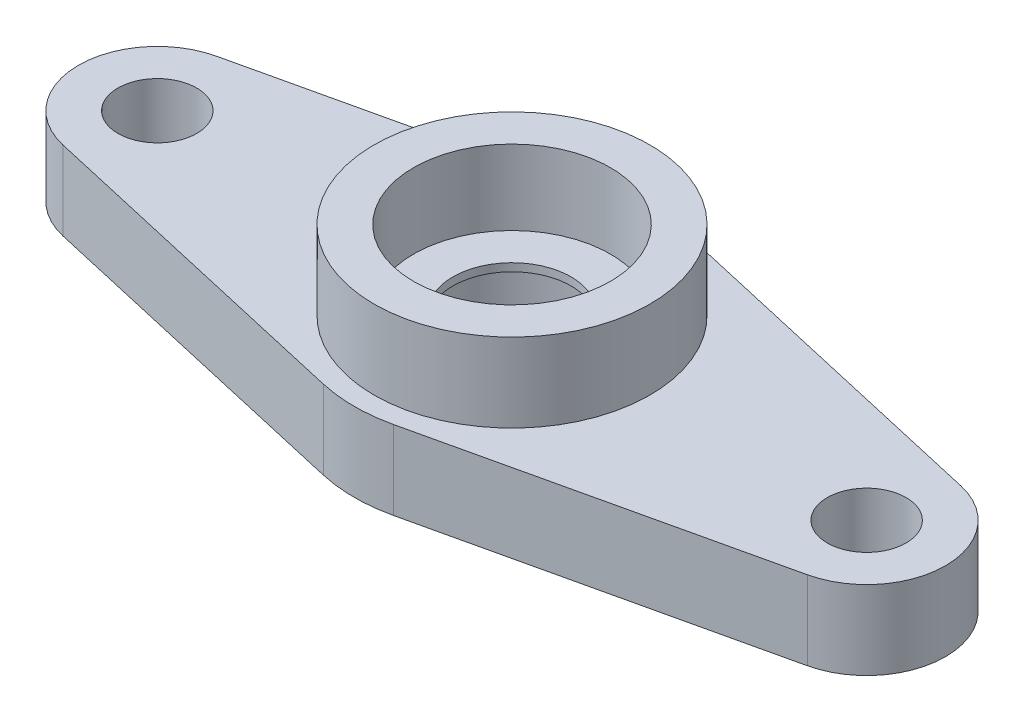
SolidWorks part; units mm, degrees
ref_plane "前基準面" through (0, 0, 0) normal (0, 0, 1) x (1, 0, 0)
ref_plane "上基準面" through (0, 0, 0) normal (0, 1, 0) x (1, 0, 0)
ref_plane "右基準面" through (0, 0, 0) normal (1, 0, 0) x (0, 0, -1)
sketch "草圖1" plane through (0, 0, 0) normal (0, 1, 0) x (1, 0, 0)
  line L0 (-9, 0) -> (9, 0) construction
  line L1 (-9.4444, 1.95) -> (-0.8889, 3.9)
  line L2 (-9.4444, -1.95) -> (-0.8889, -3.9)
  line L3 (0.8889, -3.9) -> (9.4444, -1.95)
  line L4 (0.8889, 3.9) -> (9.4444, 1.95)
  circle A0 centre (0, 0) radius 2.5
  circle A1 centre (-9, 0) radius 1
  circle A2 centre (9, 0) radius 1
  arc A3 (-0.8889, -3.9) -> (0.8889, -3.9) centre (0, 0) ccw
  arc A4 (-9.4444, 1.95) -> (-9.4444, -1.95) centre (-9, 0) ccw
  arc A5 (9.4444, -1.95) -> (9.4444, 1.95) centre (9, 0) ccw
  arc A6 (0.8889, 3.9) -> (-0.8889, 3.9) centre (0, 0) ccw
  dimension "D2" = 5
  dimension "D3" = 2
  dimension "D4" = 4
  dimension "D5" = 4
  dimension "D1" = 18
extrude "填料-伸長1" add sketch "草圖1" along normal blind 2
sketch "草圖2" plane through (0, 2, 0) normal (0, 1, 0) x (1, 0, 0)
  circle A0 centre (0, 0) radius 3.5
  circle A1 centre (0, 0) radius 2.5
  dimension "D1" = 7
extrude "填料-伸長2" add sketch "草圖2" along normal blind 2
sketch "草圖3" plane through (0, 2, 0) normal (0, 1, 0) x (1, 0, 0)
  circle A0 centre (0, 0) radius 2.5
  circle A1 centre (0, 0) radius 2.5 construction
  circle A2 centre (0, 0) radius 1.5
  dimension "D1" = 3
extrude "填料-伸長3" add sketch "草圖3" along normal blind 0.1 and the other way blind 0.1
